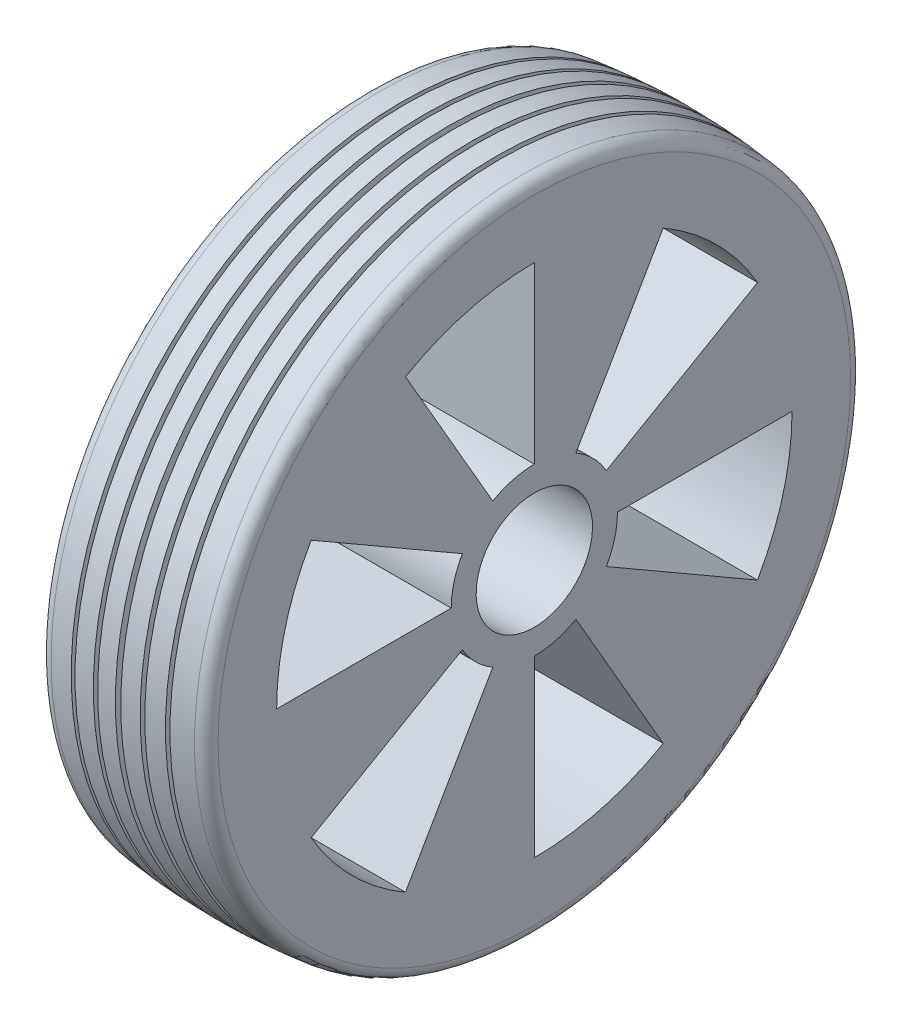
SolidWorks part; units mm, degrees
material "Plain Carbon Steel"
ref_plane "Front Plane" through (0, 0, 0) normal (0, 0, 1) x (1, 0, 0)
ref_plane "Top Plane" through (0, 0, 0) normal (0, 1, 0) x (1, 0, 0)
ref_plane "Right Plane" through (0, 0, 0) normal (1, 0, 0) x (0, 0, -1)
sketch "Sketch1" plane through (0, 0, 0) normal (0, 0, 1) x (1, 0, 0)
  line L2 (-26.1282, 0) -> (-26.1282, 25.0112)
  line L3 (24.8093, 0) -> (24.8093, 25.0112)
  line L14 (24.8093, -71.628) -> (-33.8694, -71.628)
  line L22 (24.8093, 0) -> (24.8093, -49.403)
  line L25 (-15.7742, 29.3098) -> (-15.7742, 27.3431)
  line L26 (-15.7742, 27.3431) -> (-14.5042, 27.3431)
  line L27 (-14.5042, 29.412) -> (-14.5042, 27.3431)
  line L28 (-15.499, 29.3327) -> (-14.5042, 27.3431) construction
  line L29 (-15.7742, 27.3431) -> (-14.7493, 29.393) construction
  line L33 (-8.5396, 29.7716) -> (-8.5396, 27.3431)
  line L34 (-8.5396, 27.3431) -> (-7.1745, 27.3431)
  line L35 (-7.1745, 29.826) -> (-7.1745, 27.3431)
  line L36 (-8.481, 29.7741) -> (-7.1745, 27.3431) construction
  line L37 (-8.5396, 27.3431) -> (-7.2058, 29.8249) construction
  line L42 (-26.1282, -49.403) -> (-26.1282, 0)
  line L43 (-0.6845, 28.6131) -> (-0.6845, 27.3431)
  line L45 (-0.6845, 27.3431) -> (0, 27.3431)
  line L46 (0, 27.3431) -> (0, 29.9423)
  line L52 (-1.6442, 29.9408) -> (-1.6442, 27.3431)
  line L53 (-1.6442, 27.3431) -> (-0.6845, 27.3431)
  line L54 (7.1706, 27.3431) -> (5.8055, 27.3431)
  line L55 (7.1706, 29.7733) -> (7.1706, 27.3431)
  line L56 (5.8055, 29.8275) -> (5.8055, 27.3431)
  line L58 (14.4052, 29.3132) -> (14.4052, 27.3431)
  line L59 (14.4052, 27.3431) -> (13.1352, 27.3431)
  line L60 (13.1352, 29.4151) -> (13.1352, 27.3431)
  line L63 (24.8093, -49.403) -> (24.8093, -53.848)
  line L64 (24.8093, -53.848) -> (-26.1282, -53.848)
  line L65 (-26.1282, -53.848) -> (-26.1282, -49.403)
  arc A0 (-26.1282, 25.0112) -> (-22.6248, 28.6022) centre (-22.5361, 25.0112) cw
  arc A1 (21.2075, 28.6131) -> (24.8093, 25.0112) centre (21.2075, 25.0112) cw
  arc A2 (-22.6248, 28.6022) -> (21.2075, 28.6131) centre (-0.6643, -150.5068) cw
  point P7 (-18.0278, 27.9847)
  point P10 (-18.0278, 28.9921)
revolve "Revolve2" add sketch "Sketch1" angle 360 about L14
sketch "Sketch2" plane through (24.8093, 0, 0) normal (1, 0, 0) x (0, 0, -1)
  line L0 (12.7, -49.631) -> (39.37, -3.4372)
  line L1 (21.997, -58.928) -> (68.1908, -32.258)
  line L2 (0, -46.228) -> (0, 7.112)
  line L3 (-12.7, -49.631) -> (-39.37, -3.4372)
  line L4 (-68.1908, -32.258) -> (-21.997, -58.928)
  line L5 (-25.4, -71.628) -> (-78.74, -71.628)
  line L6 (-21.997, -84.328) -> (-68.1908, -110.998)
  line L7 (-12.7, -93.625) -> (-39.37, -139.8188)
  line L8 (0, -97.028) -> (0, -150.368)
  line L9 (12.7, -93.625) -> (39.37, -139.8188)
  line L10 (21.997, -84.328) -> (68.1908, -110.998)
  line L11 (25.4, -71.628) -> (78.74, -71.628)
  circle A0 centre (0, -71.628) radius 25.4
  arc A1 (0, 7.112) -> (-39.37, -3.4372) centre (0, -71.628) ccw
  arc A2 (68.1908, -32.258) -> (39.37, -3.4372) centre (0, -71.628) ccw
  arc A3 (68.1908, -110.998) -> (78.74, -71.628) centre (0, -71.628) ccw
  arc A4 (0, -150.368) -> (39.37, -139.8188) centre (0, -71.628) ccw
  arc A5 (-68.1908, -110.998) -> (-39.37, -139.8188) centre (0, -71.628) ccw
  arc A6 (-68.1908, -32.258) -> (-78.74, -71.628) centre (0, -71.628) ccw
  point P4 (21.997, -58.928)
  point P5 (12.7, -49.631)
  point P6 (0, -46.228)
  point P7 (-12.7, -49.631)
  point P8 (-21.997, -58.928)
  point P9 (-25.4, -71.628)
  point P10 (-21.997, -84.328)
  point P11 (-12.7, -93.625)
  point P12 (0, -97.028)
  point P13 (12.7, -93.625)
  point P14 (21.997, -84.328)
  point P15 (25.4, -71.628)
  point P16 (68.1908, -32.258)
  point P17 (39.37, -3.4372)
  point P18 (0, 7.112)
  point P19 (-39.37, -3.4372)
  point P20 (-68.1908, -32.258)
  point P21 (-78.74, -71.628)
  point P22 (-68.1908, -110.998)
  point P23 (-39.37, -139.8188)
  point P24 (0, -150.368)
  point P25 (39.37, -139.8188)
  point P26 (68.1908, -110.998)
  point P27 (78.74, -71.628)
extrude "Cut-Extrude1" cut sketch "Sketch2" against normal through all contours L4 A6 L5 A0 | L2 A1 L3 A0 | L1 A2 L0 A0 | L10 A3 L11 A0 | L8 A4 L9 A0 | L6 A5 L7 A0
